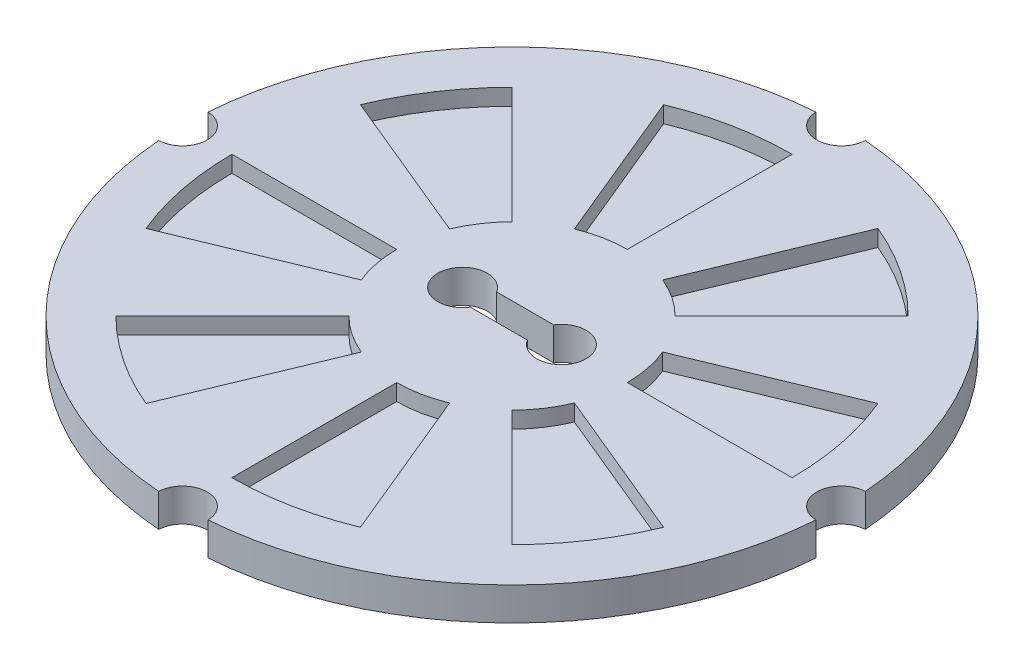
SolidWorks part; units mm, degrees
ref_plane "Front Plane" through (0, 0, 0) normal (0, 0, 1) x (1, 0, 0)
ref_plane "Top Plane" through (0, 0, 0) normal (0, 1, 0) x (1, 0, 0)
ref_plane "Right Plane" through (0, 0, 0) normal (1, 0, 0) x (0, 0, -1)
sketch "Sketch1" plane through (0, 0, 0) normal (0, 1, 0) x (1, 0, 0)
  circle A0 centre (0, 0) radius 127
  dimension "D1" = 254
extrude "Boss-Extrude1" add sketch "Sketch1" along normal blind 12.7
sketch "Sketch2" plane through (0, 12.7, 0) normal (0, 1, 0) x (1, 0, 0)
  line L0 (44.45, 0) -> (107.95, 0)
  line L1 (41.0664, 17.0103) -> (99.7328, 41.3107)
  line L2 (41.0664, -17.0103) -> (99.7328, -41.3107)
  line L3 (31.4309, -31.4309) -> (76.3322, -76.3322)
  line L4 (17.0103, -41.0664) -> (41.3107, -99.7328)
  line L5 (0, -44.45) -> (0, -107.95)
  line L6 (-17.0103, -41.0664) -> (-41.3107, -99.7328)
  line L7 (-31.4309, -31.4309) -> (-76.3322, -76.3322)
  line L8 (-41.0664, -17.0103) -> (-99.7328, -41.3107)
  line L9 (-44.45, 0) -> (-107.95, 0)
  line L10 (-41.0664, 17.0103) -> (-99.7328, 41.3107)
  line L11 (-31.4309, 31.4309) -> (-76.3322, 76.3322)
  line L12 (-17.0103, 41.0664) -> (-41.3107, 99.7328)
  line L13 (0, 44.45) -> (0, 107.95)
  line L14 (17.0103, 41.0664) -> (41.3107, 99.7328)
  line L15 (31.4309, 31.4309) -> (76.3322, 76.3322)
  arc A0 (44.45, 0) -> (41.0664, 17.0103) centre (0, 0) ccw
  arc A1 (107.95, 0) -> (99.7328, 41.3107) centre (0, 0) ccw
  arc A2 (76.3322, -76.3322) -> (99.7328, -41.3107) centre (0, 0) ccw
  arc A3 (31.4309, -31.4309) -> (41.0664, -17.0103) centre (0, 0) ccw
  arc A4 (0, -107.95) -> (41.3107, -99.7328) centre (0, 0) ccw
  arc A5 (0, -44.45) -> (17.0103, -41.0664) centre (0, 0) ccw
  arc A6 (-76.3322, -76.3322) -> (-41.3107, -99.7328) centre (0, 0) ccw
  arc A7 (-31.4309, -31.4309) -> (-17.0103, -41.0664) centre (0, 0) ccw
  arc A8 (-107.95, 0) -> (-99.7328, -41.3107) centre (0, 0) ccw
  arc A9 (-44.45, 0) -> (-41.0664, -17.0103) centre (0, 0) ccw
  arc A10 (-76.3322, 76.3322) -> (-99.7328, 41.3107) centre (0, 0) ccw
  arc A11 (-31.4309, 31.4309) -> (-41.0664, 17.0103) centre (0, 0) ccw
  arc A12 (0, 107.95) -> (-41.3107, 99.7328) centre (0, 0) ccw
  arc A13 (0, 44.45) -> (-17.0103, 41.0664) centre (0, 0) ccw
  arc A14 (76.3322, 76.3322) -> (41.3107, 99.7328) centre (0, 0) ccw
  arc A15 (31.4309, 31.4309) -> (17.0103, 41.0664) centre (0, 0) ccw
  point P37 (0, 0)
  dimension "D1" = 88.9
  dimension "D2" = 215.9
  dimension "D3" = 22.5
  dimension "D4" = 8
extrude "Cut-Extrude1" cut sketch "Sketch2" against normal blind 6.35
sketch "Sketch3" plane through (0, 12.7, 0) normal (0, 1, 0) x (1, 0, 0)
  line L0 (0, 127) -> (0, -127) construction
  line L1 (0, -6.985) -> (0, 6.985) construction
  line L2 (-10.9928, 5.08) -> (10.9928, 5.08)
  line L3 (10.9928, -5.08) -> (-10.9928, -5.08)
  line L4 (-6.985, 0) -> (6.985, 0) construction
  circle A0 centre (0, 0) radius 127 construction
  arc A1 (10.9928, -5.08) -> (10.9928, 5.08) centre (19.05, 0) ccw
  arc A2 (-10.9928, -5.08) -> (-10.9928, 5.08) centre (-19.05, 0) cw
  point P9 (0, 5.08)
  point P12 (0, -5.08)
  dimension "D3" = 19.05
  dimension "D4" = 19.05
  dimension "D1" = 5.08
  dimension "D2" = 5.08
extrude "Cut-Extrude2" cut sketch "Sketch3" against normal through all
sketch "Sketch4" plane through (0, 12.7, 0) normal (0, 1, 0) x (1, 0, 0)
  line L0 (-6.985, 0) -> (6.985, 0) construction
  line L1 (0, -6.985) -> (0, 6.985) construction
  circle A0 centre (127, 0) radius 9.525
  circle A1 centre (0, 0) radius 127 construction
  circle A2 centre (-127, 0) radius 9.525
  circle A3 centre (0, 127) radius 9.525
  circle A4 centre (0, -127) radius 9.525
  point P14 (0, 0)
  point P15 (0, 0)
  dimension "D1" = 19.05
extrude "Cut-Extrude3" cut sketch "Sketch4" against normal through all
